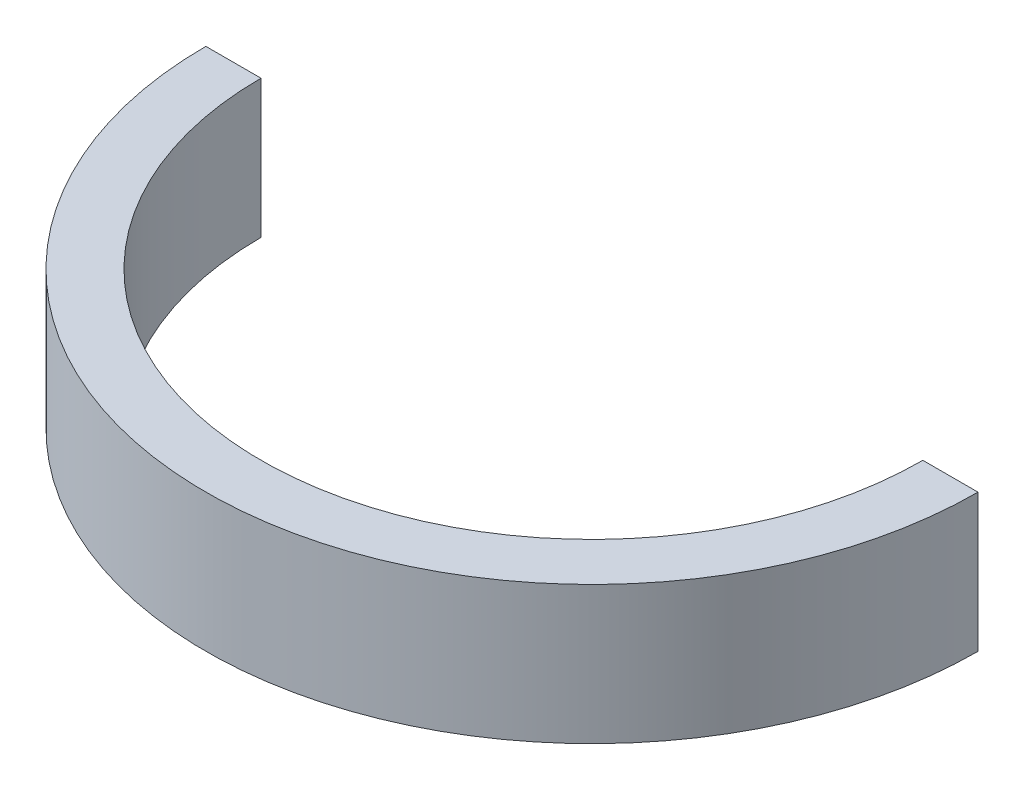
SolidWorks part; units mm, degrees
ref_plane "Front" through (0, 0, 0) normal (0, 0, 1) x (1, 0, 0)
ref_plane "Top" through (0, 0, 0) normal (0, 1, 0) x (1, 0, 0)
ref_plane "Right" through (0, 0, 0) normal (1, 0, 0) x (0, 0, -1)
sketch "草图1" plane through (0, 0, 0) normal (0, 1, 0) x (1, 0, 0)
  line L0 (-56, 0) -> (-48, 0)
  line L1 (48, 0) -> (56, 0)
  arc A0 (-56, 0) -> (56, 0) centre (0, 0) ccw
  arc A1 (-48, 0) -> (48, 0) centre (0, 0) ccw
extrude "凸台-拉伸1" add sketch "草图1" along normal blind 20
